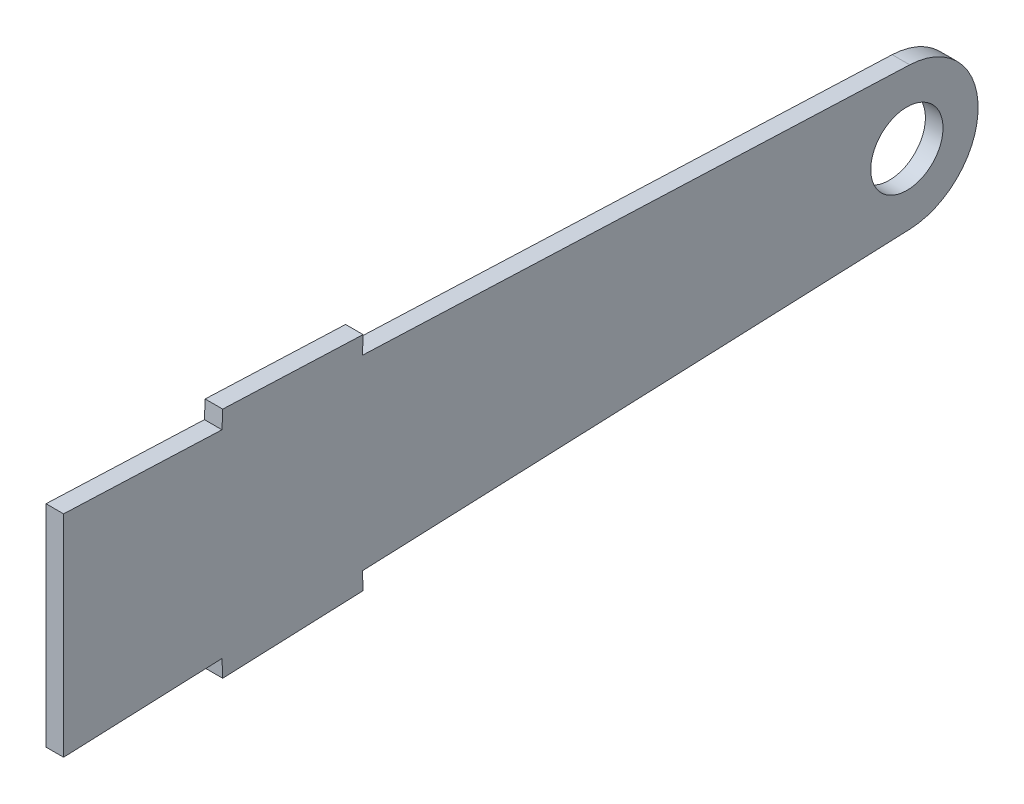
SolidWorks part; units mm, degrees
material "AISI 4130 Steel, annealed at 865C"
ref_plane "X-Y Datum" through (0, 0, 0) normal (0, 0, 1) x (1, 0, 0)
ref_plane "X-Z Datum" through (0, 0, 0) normal (0, 1, 0) x (1, 0, 0)
ref_plane "Y-Z Datum" through (0, 0, 0) normal (1, 0, 0) x (0, 0, -1)
sketch "Sketch1" plane through (0, 0, 0) normal (1, 0, 0) x (0, 0, -1)
  line L0 (0, 0) -> (-76.2, 0) construction
  line L1 (-76.2, 9.525) -> (-76.2, -9.525)
  line L2 (0.2601, 6.4336) -> (-76.2, 9.525)
  line L3 (0.2601, -6.4336) -> (-76.2, -9.525)
  circle A0 centre (0, 0) radius 3.2639
  arc A1 (0.2601, -6.4336) -> (0.2601, 6.4336) centre (0, 0) ccw
  point P7 (-76.2, 0)
  dimension "D1" = 6.5278
  dimension "D2" = 3.175
  dimension "D3" = 76.2
  dimension "D4" = 19.05
extrude "Boss-Extrude1" add sketch "Sketch1" along normal mid plane 1.5875
sketch "Sketch2" plane through (-0.7937, 0, 0) normal (-1, 0, 0) x (0, 0, 1)
  line L0 (76.2, 0) -> (-6.4389, 0) construction
  line L1 (76.2, 9.525) -> (76.2, -9.525) construction
  line L2 (34.8805, 7.8544) -> (34.8806, -7.8544) construction
  line L3 (-0.2601, 6.4336) -> (76.2, 9.525) construction
  line L4 (76.2, -9.525) -> (-0.2601, -6.4336) construction
  line L7 (55.5403, -8.6897) -> (55.5403, 8.6897) construction
  line L20 (55.5403, -8.6897) -> (61.8851, -8.9462) construction
  line L21 (61.8851, -8.9462) -> (49.1955, -8.4332)
  line L22 (61.821, -10.5324) -> (49.1313, -10.0194)
  line L23 (49.1313, -10.0194) -> (49.1955, -8.4332)
  line L24 (61.821, -10.5324) -> (61.8851, -8.9462)
  line L25 (49.1313, 10.0194) -> (49.1955, 8.4332)
  line L26 (61.821, 10.5324) -> (61.8851, 8.9462)
  line L27 (61.821, 10.5324) -> (49.1313, 10.0194)
  line L28 (61.8851, 8.9462) -> (49.1955, 8.4332)
  arc A0 (-0.2601, 6.4336) -> (-0.2601, -6.4336) centre (0, 0) ccw construction
  dimension "D1" = 6.35
  dimension "D2" = 12.7
  dimension "D3" = 1.5875
ref_plane "Plane1" through (0.7937, -9.525, 76.2) normal (0, 0.0404, -0.9992) x (-1, 0, 0)
extrude "Boss-Extrude2" add sketch "Sketch2" against normal up to surface (1.5875 mm away) contours L22 L23 L21 L24 | L27 L25 L28 L26 up to face at (0.7937, 0, 36.4252)
